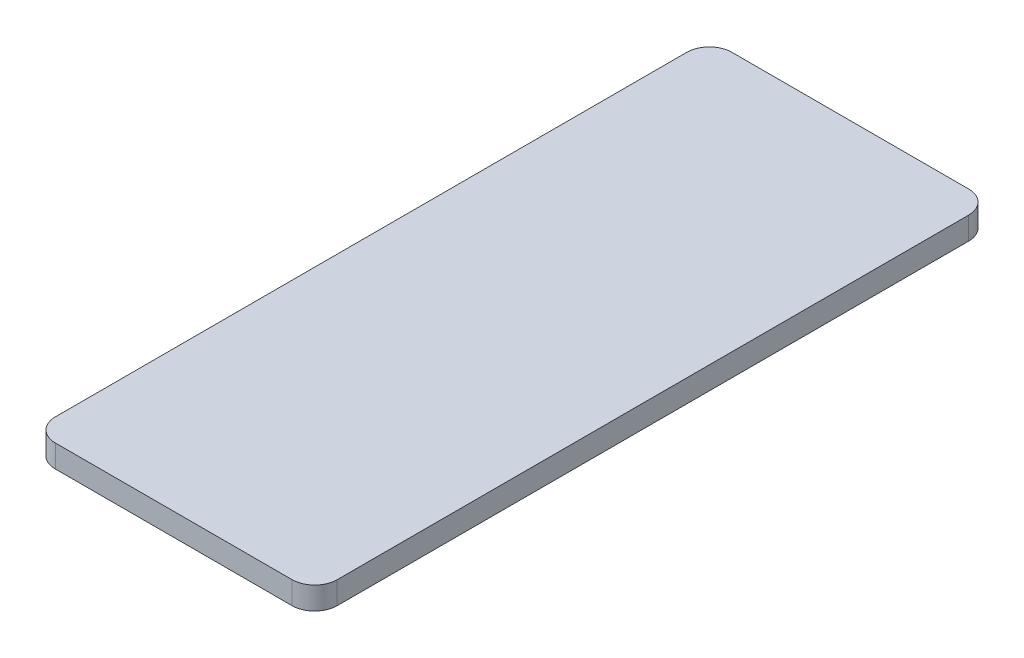
SolidWorks part; units mm, degrees
ref_plane "Front Plane" through (0, 0, 0) normal (0, 0, 1) x (1, 0, 0)
ref_plane "Top Plane" through (0, 0, 0) normal (0, 1, 0) x (1, 0, 0)
ref_plane "Right Plane" through (0, 0, 0) normal (1, 0, 0) x (0, 0, -1)
sketch "Sketch1" plane through (0, 0, 0) normal (0, 1, 0) x (1, 0, 0)
  line L1 (12.5, -30) -> (-12.5, -30)
  line L2 (12.5, -30) -> (12.5, 30)
  line L3 (12.5, 30) -> (-12.5, 30)
  line L4 (-12.5, -30) -> (-12.5, 30)
  line L5 (12.5, -30) -> (-12.5, 30) construction
  line L6 (12.5, 30) -> (-12.5, -30) construction
  point P0 (0, 0)
  dimension "D1" = 60
  dimension "D2" = 25
extrude "Boss-Extrude1" add sketch "Sketch1" along normal blind 2
fillet "Fillet1" radius 2 4 edges at (-12.5, 1, 30) (-12.5, 1, -30) (12.5, 1, -30) (12.5, 1, 30)
